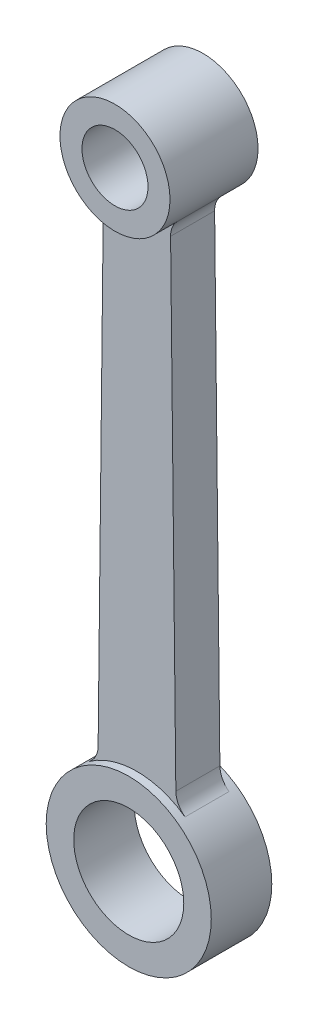
SolidWorks part; units mm, degrees
ref_plane "Front Plane" through (0, 0, 0) normal (0, 0, 1) x (1, 0, 0)
ref_plane "Top Plane" through (0, 0, 0) normal (0, 1, 0) x (1, 0, 0)
ref_plane "Right Plane" through (0, 0, 0) normal (1, 0, 0) x (0, 0, -1)
sketch "Sketch1" plane through (0, 0, 0) normal (0, 0, 1) x (1, 0, 0)
  circle A0 centre (0, 0) radius 7.5
  circle A1 centre (0, 0) radius 5
  dimension "D1" = 15
  dimension "D2" = 10
extrude "Boss-Extrude1" add sketch "Sketch1" along normal mid plane 5.5
sketch "Sketch2" plane through (0, 0, 0) normal (0, 0, 1) x (1, 0, 0)
  line L0 (0, -7.5) -> (0, 61) construction
  circle A0 centre (0, 0) radius 7.5 construction
  circle A1 centre (0, 56) radius 3
  circle A2 centre (0, 56) radius 5
  dimension "D2" = 6
  dimension "D3" = 10
  dimension "D1" = 68.5
extrude "Boss-Extrude2" add sketch "Sketch2" along normal mid plane 8 separate body
sketch "Sketch3" plane through (0, 0, 0) normal (0, 0, 1) x (1, 0, 0)
  line L0 (0, 51) -> (0, 7.5) construction
  line L1 (-3.0438, 52.0332) -> (-3.5433, 6.6102)
  line L2 (-3.5433, 6.6102) -> (-3.5433, 52.4722) construction
  line L3 (3.0438, 52.0332) -> (3.5433, 6.6102)
  circle A0 centre (0, 56) radius 5 construction
  circle A1 centre (0, 0) radius 7.5 construction
  circle A2 centre (0, 56) radius 3 construction
  arc A5 (3.5433, 6.6102) -> (-3.5433, 6.6102) centre (0, 0) ccw
  arc A6 (-3.0438, 52.0332) -> (3.0438, 52.0332) centre (0, 56) ccw
  dimension "D1" = 0.63
extrude "Boss-Extrude3" add sketch "Sketch3" along normal mid plane 4
fillet "Fillet1" radius 2 4 edges at (3.0438, 52.0332, 0) (-3.0438, 52.0332, 0) (-3.5433, 6.6102, 0) (3.5433, 6.6102, 0)
